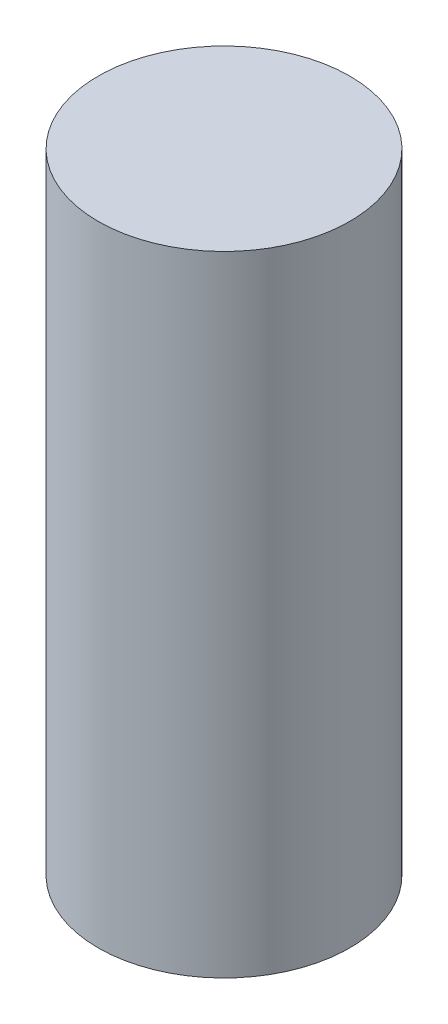
SolidWorks part; units mm, degrees
ref_plane "前视基准面" through (0, 0, 0) normal (0, 0, 1) x (1, 0, 0)
ref_plane "上视基准面" through (0, 0, 0) normal (0, 1, 0) x (1, 0, 0)
ref_plane "右视基准面" through (0, 0, 0) normal (1, 0, 0) x (0, 0, -1)
other "Configuration Table"
sketch "草图1" plane through (0, 0, 0) normal (0, 1, 0) x (1, 0, 0)
  circle A0 centre (0, 0) radius 3
  dimension "D1" = 6
extrude "凸台-拉伸1" add sketch "草图1" along normal blind 15
